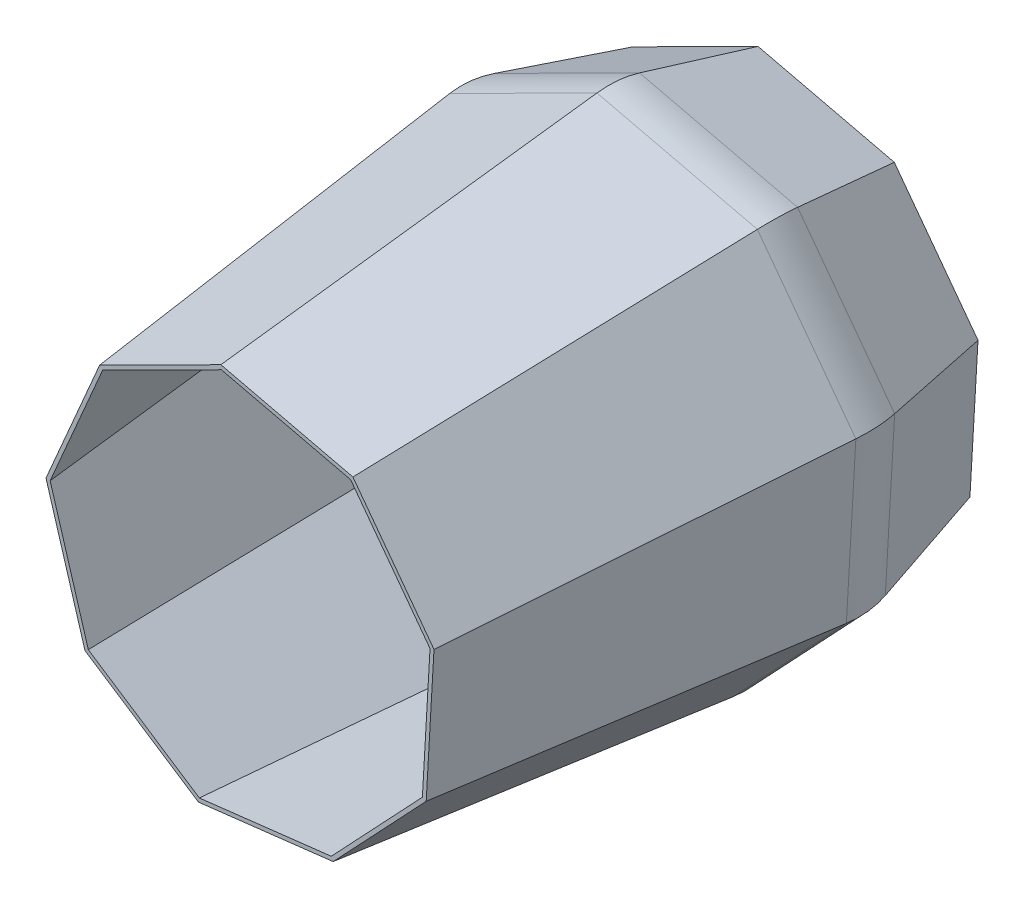
SolidWorks part; units mm, degrees
ref_plane "Alzado" through (0, 0, 0) normal (0, 0, 1) x (1, 0, 0)
ref_plane "Planta" through (0, 0, 0) normal (0, 1, 0) x (1, 0, 0)
ref_plane "Vista lateral" through (0, 0, 0) normal (1, 0, 0) x (0, 0, -1)
sketch "Croquis1" plane through (0, 0, 0) normal (0, 0, 1) x (1, 0, 0)
  line L0 (23.7738, -47.2658) -> (48.5937, -20.9262)
  line L1 (48.5937, -20.9262) -> (50.676, 15.205)
  line L2 (50.676, 15.205) -> (29.0465, 44.2217)
  line L3 (29.0465, 44.2217) -> (-6.1742, 52.5465)
  line L4 (-6.1742, 52.5465) -> (-38.506, 36.2842)
  line L5 (-38.506, 36.2842) -> (-52.8203, 3.0442)
  line L6 (-52.8203, 3.0442) -> (-42.4195, -31.6203)
  line L7 (-42.4195, -31.6203) -> (-12.1701, -51.4893)
  line L8 (-12.1701, -51.4893) -> (23.7738, -47.2658)
  circle A0 centre (0, 0) radius 49.7172 construction
extrude "Saliente-Extruir4" add sketch "Croquis1" along normal blind 35 draft 15 draft outward yes
ref_plane "Plano2" through (0, 0, 35) normal (0, 0, -1) x (-1, 0, 0)
sketch "Croquis12" plane through (0, 0, 35) normal (0, 0, -1) x (-1, 0, 0)
  line L1 (50.4211, -37.5849) -> (62.7839, 3.6184)
  line L2 (62.7839, 3.6184) -> (45.7694, 43.1286)
  line L3 (45.7694, 43.1286) -> (7.3389, 62.4584)
  line L4 (7.3389, 62.4584) -> (-34.5256, 52.5633)
  line L5 (-34.5256, 52.5633) -> (-60.2351, 18.0732)
  line L6 (-60.2351, 18.0732) -> (-57.76, -24.8735)
  line L7 (-57.76, -24.8735) -> (-28.2583, -56.1816)
  line L8 (-28.2583, -56.1816) -> (14.4657, -61.2017)
  line L9 (14.4657, -61.2017) -> (50.4211, -37.5849)
  circle A0 centre (0, 0) radius 59.0955 construction
extrude "Saliente-Extruir5" add sketch "Croquis12" against normal blind 104 draft 6
fillet "Redondeo1" radius 30 9 edges at (-32.4434, -49.3933, 35) (-56.6025, -16.9832, 35) (-54.2766, 23.3735, 35) (-26.5541, 52.7935, 35) (13.5933, 57.5108, 35) (47.3803, 35.3182, 35) (58.9976, -3.4002, 35) (43.0092, -40.5276, 35) (6.8963, -58.6917, 35)
shell "Vaciado1" thickness 1
